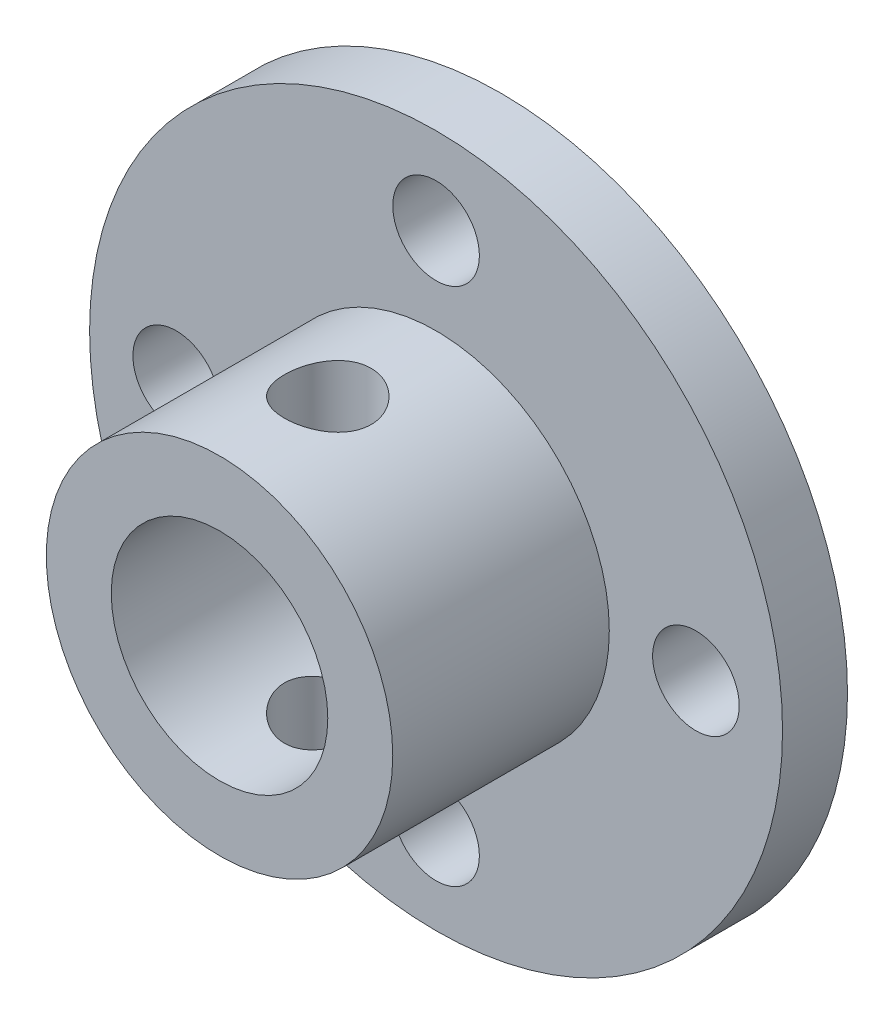
SolidWorks part; units mm, degrees
ref_plane "前视基准面" through (0, 0, 0) normal (0, 0, 1) x (1, 0, 0)
ref_plane "上视基准面" through (0, 0, 0) normal (0, 1, 0) x (1, 0, 0)
ref_plane "右视基准面" through (0, 0, 0) normal (1, 0, 0) x (0, 0, -1)
other "Configuration Table"
sketch "草图1" plane through (0, 0, 0) normal (0, 0, 1) x (1, 0, 0)
  circle A0 centre (0, 0) radius 16
  dimension "D1" = 32
extrude "凸台-拉伸1" add sketch "草图1" along normal blind 3
sketch "草图2" plane through (0, 0, 3) normal (0, 0, 1) x (1, 0, 0)
  circle A0 centre (0, 0) radius 8
  dimension "D1" = 16
extrude "凸台-拉伸2" add sketch "草图2" along normal blind 10
sketch "草图3" plane through (0, 0, 13) normal (0, 0, 1) x (1, 0, 0)
  circle A0 centre (0, 0) radius 5
  dimension "D1" = 10
extrude "切除-拉伸1" cut sketch "草图3" against normal through all
sketch "草图4" plane through (0, 0, 3) normal (0, 0, 1) x (1, 0, 0)
  line L0 (0, 0) -> (0, 12) construction
  circle A0 centre (0, 12) radius 2
  circle A1 centre (12, 0) radius 2
  circle A2 centre (0, -12) radius 2
  circle A3 centre (-12, 0) radius 2
  point P3 (0, 0)
  point P13 (0, 0)
  dimension "D1" = 12
  dimension "D2" = 4
  dimension "D3" = 4
extrude "切除-拉伸2" cut sketch "草图4" against normal through all
sketch "草图5" plane through (0, 0, 0) normal (0, 1, 0) x (1, 0, 0)
  line L0 (0, -8) -> (0, 0) construction
  circle A0 centre (0, -8) radius 2
  dimension "D1" = 4
  dimension "D2" = 8
extrude "切除-拉伸3" cut sketch "草图5" against normal through all and the other way through all
